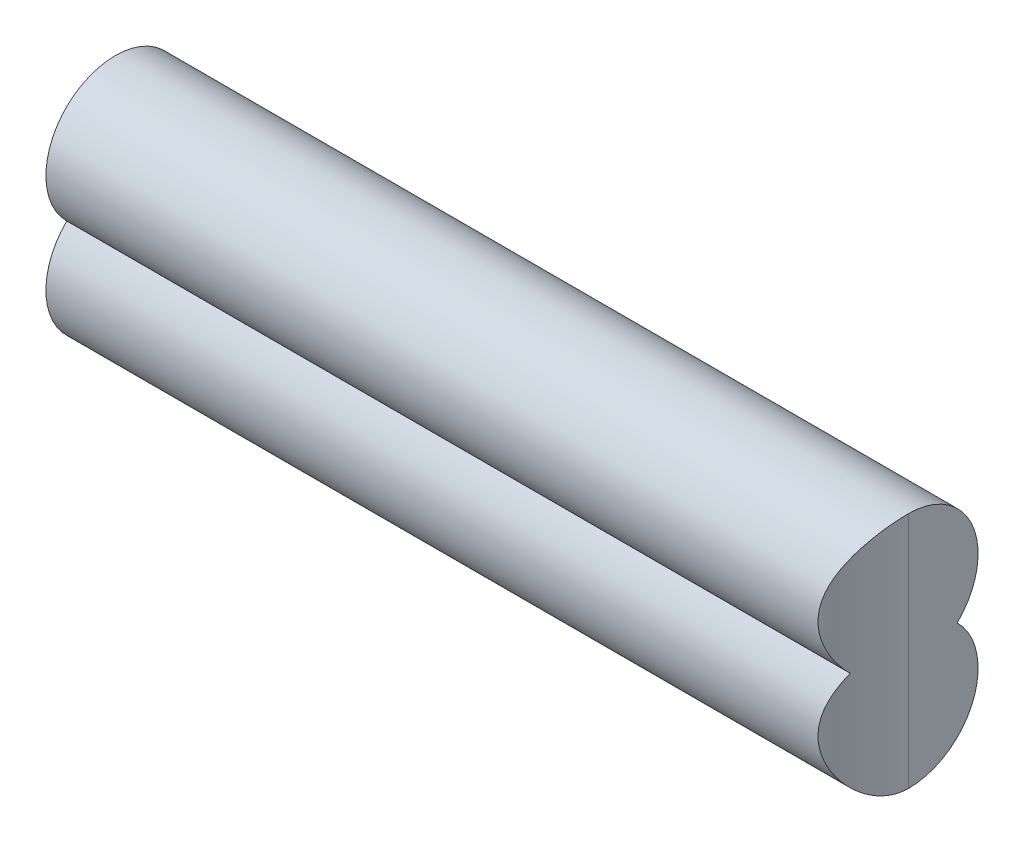
SolidWorks part; units mm, degrees
ref_plane "Front Plane" through (0, 0, 0) normal (0, 0, 1) x (1, 0, 0)
ref_plane "Top Plane" through (0, 0, 0) normal (0, 1, 0) x (1, 0, 0)
ref_plane "Right Plane" through (0, 0, 0) normal (1, 0, 0) x (0, 0, -1)
sketch "Sketch2" plane through (0, 0, 0) normal (1, 0, 0) x (0, 0, -1)
  line L1 (6.35, 6.35) -> (-6.35, 6.35)
  line L2 (6.35, 6.35) -> (6.35, -6.35)
  line L3 (6.35, -6.35) -> (-6.35, -6.35)
  line L4 (-6.35, 6.35) -> (-6.35, -6.35)
  line L5 (6.35, 6.35) -> (-6.35, -6.35) construction
  line L6 (6.35, -6.35) -> (-6.35, 6.35) construction
  point P0 (0, 0)
  dimension "D1" = 12.7
  dimension "D2" = 12.7
extrude "Boss-Extrude1" add sketch "Sketch2" along normal blind 40.64
fillet "Fillet1" radius 6.35 1 edges at (40.64, 0, 6.35)
sketch "Sketch3" plane through (0, 0, 0) normal (-1, 0, 0) x (0, 0, 1)
  line L0 (0, -6.35) -> (0, 6.35) construction
  line L1 (6.35, -6.35) -> (-6.35, -6.35) construction
  line L2 (-6.35, 6.35) -> (6.35, 6.35) construction
  line L3 (6.35, 0) -> (-6.35, 0) construction
  line L4 (6.35, 6.35) -> (6.35, -6.35) construction
  line L5 (-6.35, -6.35) -> (-6.35, 6.35) construction
  line L7 (6.35, -6.35) -> (-6.35, -6.35)
  line L8 (6.35, -6.35) -> (6.35, 6.35)
  line L9 (6.35, 6.35) -> (-6.35, 6.35)
  line L10 (-6.35, -6.35) -> (-6.35, 6.35)
  line L11 (6.35, -6.35) -> (-6.35, 6.35) construction
  line L12 (6.35, 6.35) -> (-6.35, -6.35) construction
  circle A0 centre (0, -2.54) radius 3.556
  circle A1 centre (0, 2.54) radius 3.556
  point P16 (0, 0)
  line M3 (6.35, -6.35) -> (6.35, 6.35)
  line M4 (6.35, 6.35) -> (-6.35, 6.35)
  line M5 (-6.35, 6.35) -> (-6.35, -6.35)
  line M6 (-6.35, -6.35) -> (6.35, -6.35)
  dimension "D1" = 7.112
  dimension "D2" = 7.112
  dimension "D3" = 2.54
  dimension "D4" = 2.54
extrude "Cut-Extrude2" cut sketch "Sketch3" against normal through all contours A1 A0 M6 M3 M4 M5
